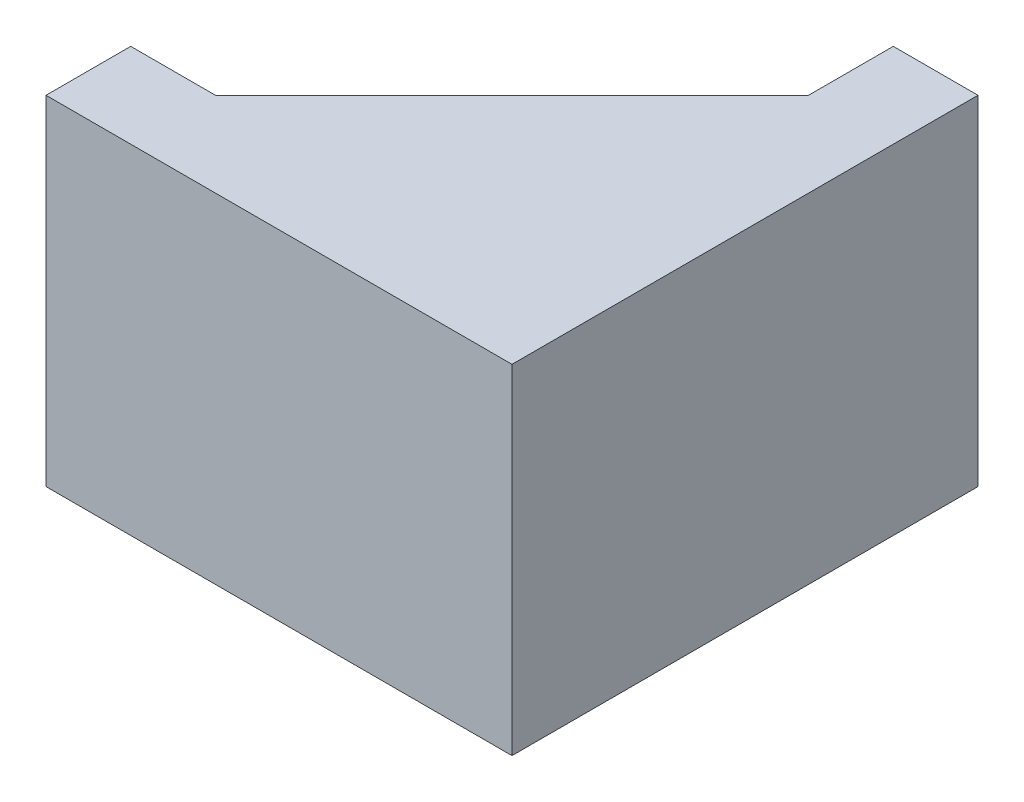
SolidWorks part; units mm, degrees
ref_plane "Front Plane" through (0, 0, 0) normal (0, 0, 1) x (1, 0, 0)
ref_plane "Top Plane" through (0, 0, 0) normal (0, 1, 0) x (1, 0, 0)
ref_plane "Right Plane" through (0, 0, 0) normal (1, 0, 0) x (0, 0, -1)
sketch "Sketch1" plane through (0, 0, 0) normal (0, 1, 0) x (1, 0, 0)
  line L0 (0, 0) -> (-27.5, 0)
  line L1 (0, 0) -> (0, 27.5)
  line L2 (-27.5, 0) -> (-27.5, 5)
  line L3 (-27.5, 5) -> (-22.5, 5)
  line L4 (0, 27.5) -> (-5, 27.5)
  line L5 (-5, 27.5) -> (-5, 22.5)
  line L6 (-22.5, 5) -> (-5, 22.5)
  dimension "D1" = 27.5
  dimension "D2" = 5
extrude "Boss-Extrude1" add sketch "Sketch1" along normal blind 20
